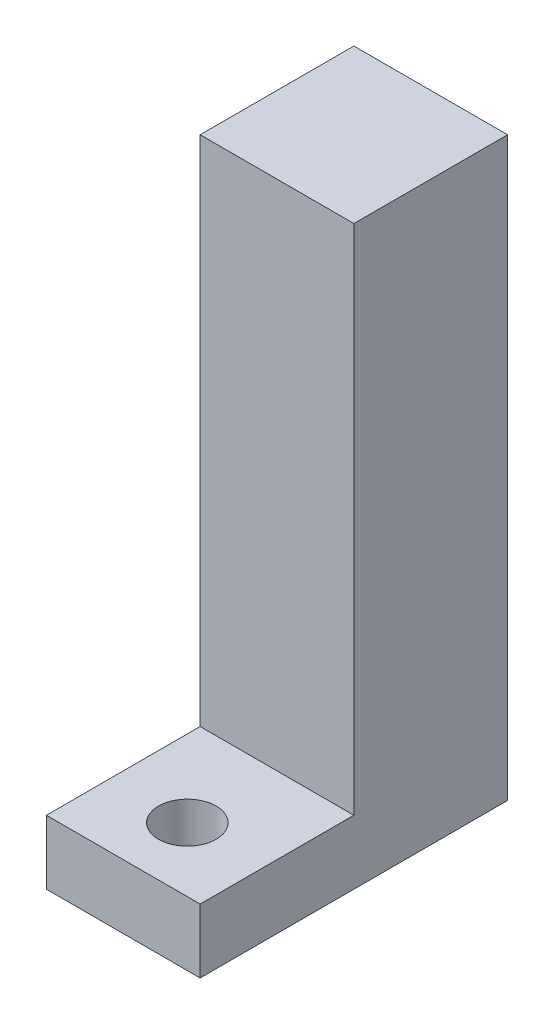
SolidWorks part; units mm, degrees
ref_plane "Front Plane" through (0, 0, 0) normal (0, 0, 1) x (1, 0, 0)
ref_plane "Top Plane" through (0, 0, 0) normal (0, 1, 0) x (1, 0, 0)
ref_plane "Right Plane" through (0, 0, 0) normal (1, 0, 0) x (0, 0, -1)
other "Configuration Table"
sketch "Sketch1" plane through (0, 0, 0) normal (0, 1, 0) x (1, 0, 0)
  line L0 (-6, -6) -> (6, -6)
  line L1 (6, -6) -> (6, 6)
  line L2 (6, 6) -> (-6, 6)
  line L3 (-6, 6) -> (-6, -6)
extrude "Leg" add sketch "Sketch1" along normal blind 45 from offset 45
sketch "Sketch2" plane through (0, 0, 0) normal (0, 1, 0) x (1, 0, 0)
  line L0 (-6, -18) -> (6, -18)
  line L1 (6, -18) -> (6, 0)
  line L2 (6, 0) -> (-6, 0)
  line L3 (-6, 0) -> (-6, -18)
extrude "Foot_Pad" add sketch "Sketch2" along normal blind 5 from offset 45
sketch "Sketch3" plane through (0, 0, 0) normal (0, 1, 0) x (1, 0, 0)
  circle A0 centre (0, -13) radius 2.25
  dimension "D1" = 4.5
extrude "Foot_Hole_M4" cut sketch "Sketch3" along normal blind 6 from offset 45.5
equation "\"Jar_OD\"= 90  'ASSUMED - Part G fallback - jar outer diameter"
equation "\"Jar_H\"= 120  'ASSUMED - Part G fallback - jar height"
equation "\"Pump_L\"= 45  'ASSUMED - Part G fallback"
equation "\"Pump_W\"= 24  'ASSUMED - Part G fallback"
equation "\"Pump_H\"= 33  'ASSUMED - Part G fallback"
equation "\"Pump_Outlet_OD\"= 7.5  'ASSUMED - Part G fallback"
equation "\"Tube_OD\"= 8  'ASSUMED - Part G fallback"
equation "\"Tube_ID\"= 6  'ASSUMED - Part G fallback"
equation "\"TDS_Body_Dia\"= 12  'ASSUMED - Part G fallback"
equation "\"TDS_Wet_Len\"= 45  'ASSUMED - Part G fallback - length in water"
equation "\"DS_Tube_Dia\"= 6  'ASSUMED - Part G fallback"
equation "\"DS_Tube_Len\"= 50  'ASSUMED - Part G fallback"
equation "\"ORP_Body_Dia\"= 12  'ASSUMED - Part G fallback"
equation "\"ORP_Body_Len\"= 150  'ASSUMED - Part G fallback"
equation "\"ORP_Cap_Dia\"= 16  'ASSUMED - Part G fallback"
equation "\"Turb_W\"= 33  'ASSUMED - Part G fallback - head width"
equation "\"Turb_D\"= 28  'ASSUMED - Part G fallback - head depth"
equation "\"Turb_H\"= 30  'ASSUMED - Part G fallback - head height"
equation "\"Turb_Slot_W\"= 10  'ASSUMED - Part G fallback - slot width"
equation "\"Flow_L\"= 62  'ASSUMED - Part G fallback YF-S201"
equation "\"Flow_W\"= 36  'ASSUMED - Part G fallback"
equation "\"Flow_H\"= 35  'ASSUMED - Part G fallback"
equation "\"Thread_G12_OD\"= 20.955  'ASSUMED - Part G fallback thread G1/2 (major diameter)"
equation "\"Valve_L\"= 75  'ASSUMED - Part G fallback"
equation "\"Valve_W\"= 45  'ASSUMED - Part G fallback"
equation "\"Valve_H\"= 60  'ASSUMED - Part G fallback"
equation "\"Tee_L\"= 40  'ASSUMED - Part G fallback - overall length"
equation "\"Tee_Branch_L\"= 25  'ASSUMED - Part G fallback"
equation "\"Tee_OD\"= 12  'ASSUMED - Part G fallback"
equation "\"LED_Board_L\"= 20  'ASSUMED - Part G fallback"
equation "\"LED_Board_W\"= 20  'ASSUMED - Part G fallback - LED at centre"
equation "\"GUVA_L\"= 20  'ASSUMED - Part G fallback"
equation "\"GUVA_W\"= 12  'ASSUMED - Part G fallback - sensor at centre"
equation "\"Reed_L\"= 27  'ASSUMED - Part G fallback MC-38 half"
equation "\"Reed_W\"= 14  'ASSUMED - Part G fallback"
equation "\"Reed_H\"= 8  'ASSUMED - Part G fallback"
equation "\"ESP_L\"= 51  'ASSUMED - Part G fallback"
equation "\"ESP_W\"= 28  'ASSUMED - Part G fallback"
equation "\"TFT_L\"= 58  'ASSUMED - Part G fallback - board"
equation "\"TFT_W\"= 35  'ASSUMED - Part G fallback - board"
equation "\"TFT_Win_L\"= 35  'ASSUMED - Part G fallback - visible window"
equation "\"TFT_Win_W\"= 28  'ASSUMED - Part G fallback - visible window"
equation "\"Relay_L\"= 50  'ASSUMED - Part G fallback"
equation "\"Relay_W\"= 26  'ASSUMED - Part G fallback"
equation "\"Relay_H\"= 19  'ASSUMED - Part G fallback"
equation "\"Mosfet_L\"= 34  'ASSUMED - Part G fallback"
equation "\"Mosfet_W\"= 17  'ASSUMED - Part G fallback"
equation "\"Mosfet_H\"= 12  'ASSUMED - Part G fallback"
equation "\"TDS_Board_L\"= 42  'ASSUMED - Part G fallback"
equation "\"TDS_Board_W\"= 32  'ASSUMED - Part G fallback"
equation "\"Turb_Board_L\"= 38  'ASSUMED - Part G fallback"
equation "\"Turb_Board_W\"= 28  'ASSUMED - Part G fallback"
equation "\"BNC_Thread_Dia\"= 9.5  'ASSUMED - Part G fallback"
equation "\"Plate_L\"= 420  'ASSUMED - Part G fallback"
equation "\"Plate_W\"= 297  'ASSUMED - Part G fallback"
equation "\"Plate_T\"= 6  'ASSUMED - Part G fallback"
equation "\"Booster_L\"= 150  'ASSUMED - Part G fallback - booster pump"
equation "\"Booster_W\"= 95  'ASSUMED - Part G fallback"
equation "\"Booster_H\"= 100  'ASSUMED - Part G fallback"
equation "\"PTube_OD\"= 6.35  'ASSUMED - Part G fallback - product tube 1/4 inch"
equation "\"Qz_Out\"= 12  'ASSUMED - Part G fallback - quartz channel outside square"
equation "\"Qz_Path\"= 10  'ASSUMED - Part G fallback - quartz channel inside light path"
equation "\"Qz_L\"= 40  'ASSUMED - Part G fallback - quartz channel length"
equation "\"LED860_Dia\"= 5  'ASSUMED - Part G fallback - 860 nm LED"
equation "\"BPW_L\"= 5.4  'ASSUMED - Part G fallback - BPW34"
equation "\"BPW_W\"= 4.3  'ASSUMED - Part G fallback - BPW34"
equation "\"Cart_Dia\"= 50  'ASSUMED - Part G fallback - sediment and pre-carbon cartridges"
equation "\"Cart_L\"= 255  'ASSUMED - Part G fallback"
equation "\"UF_Dia\"= 50  'ASSUMED - Part G fallback - UF cartridge"
equation "\"UF_L\"= 260  'ASSUMED - Part G fallback"
equation "\"RO_Dia\"= 62  'ASSUMED - Part G fallback - RO membrane housing"
equation "\"RO_L\"= 300  'ASSUMED - Part G fallback"
equation "\"UVC_Dia\"= 40  'ASSUMED - Part G fallback - UV-C chamber"
equation "\"UVC_L\"= 300  'ASSUMED - Part G fallback"
equation "\"Tank_W\"= 260  'ASSUMED - Part G fallback - storage tank"
equation "\"Tank_D\"= 160  'ASSUMED - Part G fallback"
equation "\"Tank_H\"= 300  'ASSUMED - Part G fallback"
equation "\"Cab_W\"= 400  'ASSUMED - Part G fallback - purifier cabinet"
equation "\"Cab_D\"= 270  'ASSUMED - Part G fallback"
equation "\"Cab_H\"= 560  'ASSUMED - Part G fallback"
equation "\"ORP_Board_L\"= 40  'ASSUMED - Part G fallback - ORP buffer board"
equation "\"ORP_Board_W\"= 30  'ASSUMED - Part G fallback"
equation "\"Opt_Board_L\"= 50  'ASSUMED - Part G fallback - optical front-end board"
equation "\"Opt_Board_W\"= 40  'ASSUMED - Part G fallback"
equation "\"Buck_L\"= 43  'ASSUMED - Part G fallback - 12 V to 5 V buck module"
equation "\"Buck_W\"= 21  'ASSUMED - Part G fallback"
equation "\"Buck_H\"= 14  'ASSUMED - Part G fallback"
equation "\"BB_L\"= 165  'ASSUMED - Part G fallback - breadboard (As_Built_R3 only)"
equation "\"BB_W\"= 55  'ASSUMED - Part G fallback"
equation "\"BB_H\"= 10  'ASSUMED - Part G fallback"
equation "\"Cuv_W\"= 12.5  'ASSUMED - old R3 cuvette (station suppressed in SS4)"
equation "\"Cuv_D\"= 12.5  'ASSUMED - old R3 cuvette (station suppressed in SS4)"
equation "\"Cuv_H\"= 45  'ASSUMED - old R3 cuvette (station suppressed in SS4)"
equation "\"Probe_Clr\"= 0.3  'DESIGN VALUE - Part C rule 3 - printed probe hole = diameter + 0.3"
equation "\"Label_H\"= 0.6  'DESIGN VALUE - Part D - raised label height"
equation "\"D1@Leg\" = 45.0"
